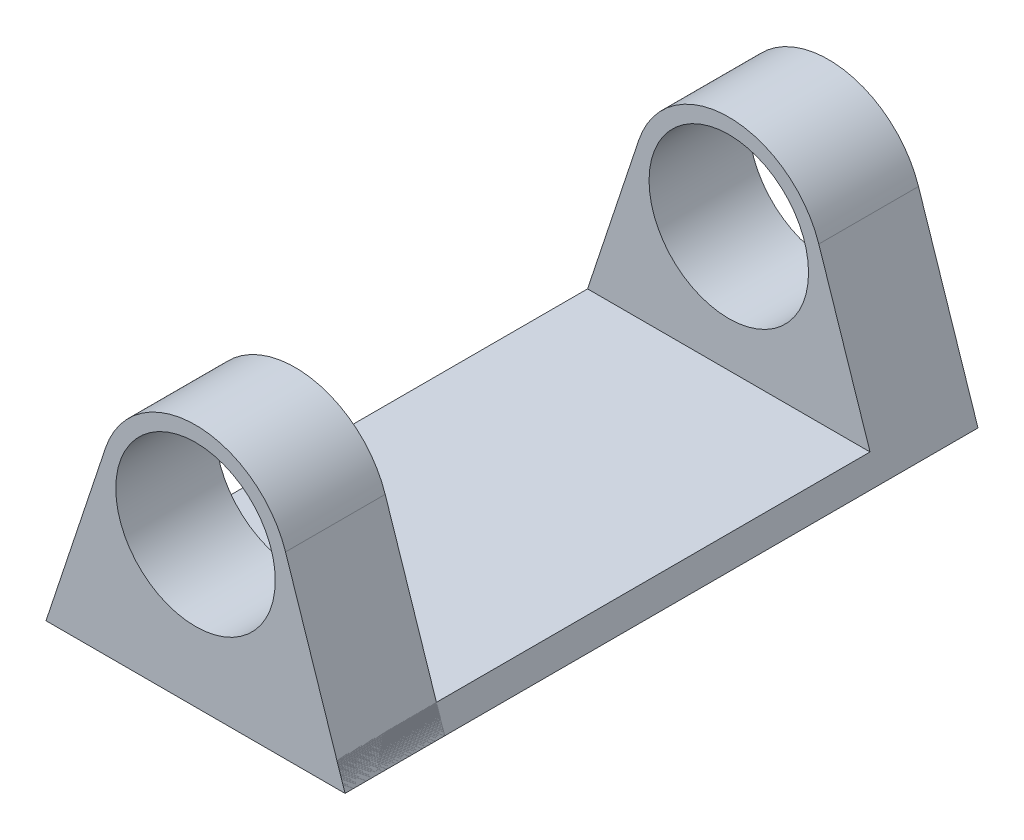
SolidWorks part; units mm, degrees
ref_plane "Front Plane" through (0, 0, 0) normal (0, 0, 1) x (1, 0, 0)
ref_plane "Top Plane" through (0, 0, 0) normal (0, 1, 0) x (1, 0, 0)
ref_plane "Right Plane" through (0, 0, 0) normal (1, 0, 0) x (0, 0, -1)
sketch "Sketch5" plane through (0, 0, 0) normal (0, 0, 1) x (1, 0, 0)
  line L0 (-5.903, -6.0322) -> (-6.5, -7.8317)
  line L1 (-6.5, -7.8317) -> (-3.5, -7.8317)
  line L2 (-4.097, -6.0322) -> (-3.5, -7.8317)
  circle A0 centre (-5, -6.3317) radius 0.8
  arc A1 (-4.097, -6.0322) -> (-5.903, -6.0322) centre (-5, -6.3317) ccw
  point P2 (0, 0)
  point P12 (0, -5.8317)
  dimension "D2" = 1.6
  dimension "D1" = 3
  dimension "D3" = 1.5
extrude "Boss-Extrude2" add sketch "Sketch5" against normal blind 1 and the other way blind 0.0001
ref_plane "Plane1" through (0, 0, 5.3501) normal (0, 0, 1) x (1, 0, 0)
sketch "Sketch7" plane through (0, 0, 5.3501) normal (0, 0, 1) x (1, 0, 0)
  line L0 (-5.903, -6.0322) -> (-6.5, -7.8317)
  line L1 (-6.5, -7.8317) -> (-3.5, -7.8317)
  line L2 (-4.097, -6.0322) -> (-3.5, -7.8317)
  circle A0 centre (-5, -6.3317) radius 0.8
  arc A1 (-4.097, -6.0322) -> (-5.903, -6.0322) centre (-5, -6.3317) ccw
  dimension "D2" = 1.6
  dimension "D1" = 3
  dimension "D3" = 1.5
extrude "Boss-Extrude3" add sketch "Sketch7" against normal blind 1 separate body
ref_plane "Plane3" through (0, 0, 0.0001) normal (0, 0, 1) x (1, 0, 0)
sketch "Sketch8" plane through (0, 0, 0) normal (0, 0, 1) x (1, 0, 0)
  line L0 (-5.2981, -4.2086) -> (-6.5, -7.8317)
  line L1 (-6.5, -7.8317) -> (-3.5, -7.8317)
  line L2 (-4.7019, -4.2086) -> (-3.5, -7.8317)
  line L3 (-5, -7.8317) -> (-5, -7.5817)
  line L6 (-5, -7.5817) -> (-6.4171, -7.5817)
  line L7 (-6.4171, -7.5817) -> (-5, -7.5817)
  line L8 (-5, -7.5817) -> (-3.5829, -7.5817)
  circle A0 centre (-5, -4.3075) radius 0.8
  arc A1 (-4.7019, -4.2086) -> (-5.2981, -4.2086) centre (-5, -4.3075) ccw
  point P12 (0, -5.8317)
  dimension "D2" = 1.6
  dimension "D1" = 3
extrude "Boss-Extrude4" add sketch "Sketch8" along normal blind 5.35
ref_plane "Revolute_Stand_Mid_Plane" through (0, 0, 2.1751) normal (0, 0, 1) x (1, 0, 0)
